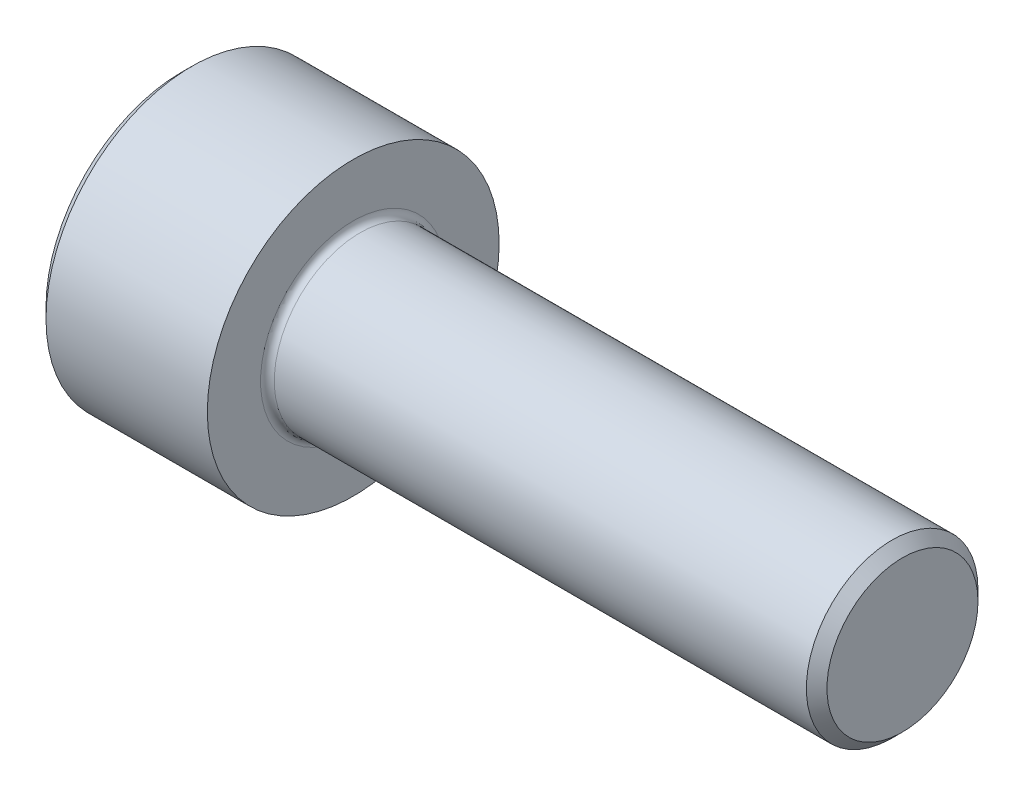
SolidWorks part; units mm, degrees
material "Galvanized Steel"
ref_plane "Plano frontal" through (0, 0, 0) normal (0, 0, 1) x (1, 0, 0)
ref_plane "Plano superior" through (0, 0, 0) normal (0, 1, 0) x (1, 0, 0)
ref_plane "Plano direito" through (0, 0, 0) normal (1, 0, 0) x (0, 0, -1)
ref_plane "Plano1" through (0, 0, 0) normal (0, 0, -1) x (-1, 0, 0)
sketch "Esboço1" plane through (0, 0, 0) normal (0, 0, -1) x (-1, 0, 0)
  line L0 (-5, 4.25) -> (-5, 0)
  line L1 (-5, 0) -> (0, 0)
  line L2 (0, 0) -> (0, 4.25)
  line L3 (0, 4.25) -> (-5, 4.25)
  line L4 (-5, 0) -> (0, 0) construction
revolve "Revolução1" add sketch "Esboço1" angle 360 about L4
sketch "Esboço2" plane through (5, 0, 0) normal (1, 0, 0) x (0, 0, -1)
  circle A0 centre (0, 0) radius 2.5
extrude "Ressalto-extrusão1" add sketch "Esboço2" along normal blind 16
sketch "Esboço3" plane through (0, 0, 0) normal (-1, 0, 0) x (0, 0, 1)
  line L0 (0, -2.3579) -> (2.042, -1.1789)
  line L1 (2.042, -1.1789) -> (2.042, 1.1789)
  line L2 (2.042, 1.1789) -> (0, 2.3579)
  line L3 (0, 2.3579) -> (-2.042, 1.1789)
  line L4 (-2.042, 1.1789) -> (-2.042, -1.1789)
  line L5 (-2.042, -1.1789) -> (0, -2.3579)
extrude "Corte-extrusão1" cut sketch "Esboço3" against normal blind 2.5
sketch "Esboço4" plane through (0, 0, 0) normal (0, 0, 1) x (1, 0, 0)
  line L0 (2.5, 2.042) -> (2.5, 0)
  line L1 (2.5, 0) -> (3.6789, 0)
  line L2 (3.6789, 0) -> (2.5, 2.042)
  line L3 (2.5, 0) -> (3.6789, 0) construction
revolve "Corte-Revolução1" cut sketch "Esboço4" angle 360 about L3
chamfer "Chanfro1" distance 0.3 angle 45 2 edges at (21, 0, -2.5) (0, 0, 4.25)
fillet "Filete1" radius 0.2 1 edges at (5, 0, -2.5)
sketch "Sketch1" plane through (0, 0, 0) normal (0, 1, 0) x (1, 0, 0)
  line L0 (0, 2.36) -> (1.3625, 0)
  line L1 (0, 3.95) -> (0, -3.95) construction
  line L3 (0, 0) -> (0, 2.36)
  line L4 (0, 0) -> (1.3625, 0)
  line L6 (1.3625, 0) -> (3.6789, 0) construction
  line L7 (3.6789, 0) -> (2.5, 2.042) construction
  dimension "D1" = 4.72
revolve "Cut-Revolve1" cut sketch "Sketch1" angle 360 about L6
